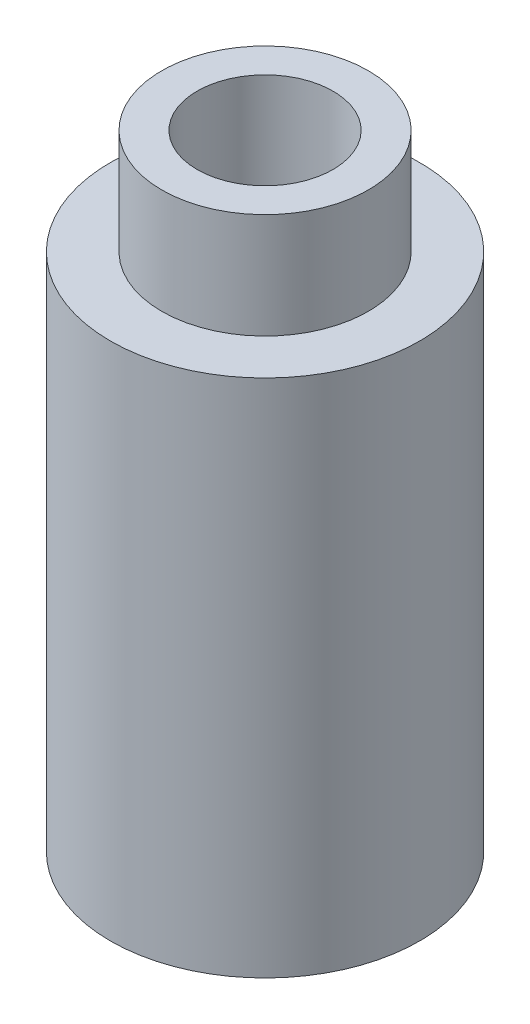
SolidWorks part; units mm, degrees
ref_plane "Front Plane" through (0, 0, 0) normal (0, 0, 1) x (1, 0, 0)
ref_plane "Top Plane" through (0, 0, 0) normal (0, 1, 0) x (1, 0, 0)
ref_plane "Right Plane" through (0, 0, 0) normal (1, 0, 0) x (0, 0, -1)
sketch "Sketch1" plane through (0, 0, 0) normal (0, 1, 0) x (1, 0, 0)
  circle A0 centre (0, 0) radius 9.4488
  dimension "D1" = 18.8976
extrude "Boss-Extrude1" add sketch "Sketch1" along normal blind 31.75
sketch "Sketch2" plane through (0, 31.75, 0) normal (0, 1, 0) x (1, 0, 0)
  circle A0 centre (0, 0) radius 6.3119
  dimension "D1" = 12.6238
extrude "Boss-Extrude2" add sketch "Sketch2" along normal blind 6.4262
sketch "Sketch3" plane through (0, 38.1762, 0) normal (0, 1, 0) x (1, 0, 0)
  circle A0 centre (0, 0) radius 4.1529
  dimension "D1" = 8.3058
extrude "Cut-Extrude1" cut sketch "Sketch3" against normal through all
